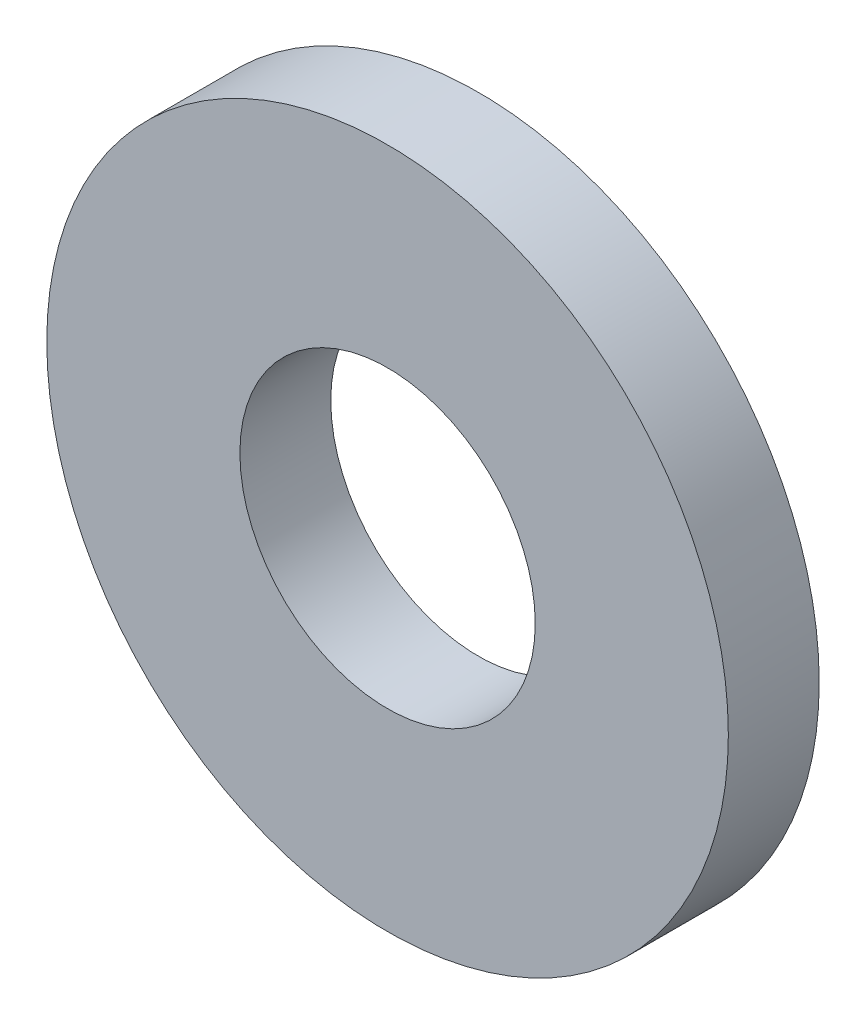
SolidWorks part; units mm, degrees
ref_plane "Alzado" through (0, 0, 0) normal (0, 0, 1) x (1, 0, 0)
ref_plane "Planta" through (0, 0, 0) normal (0, 1, 0) x (1, 0, 0)
ref_plane "Vista lateral" through (0, 0, 0) normal (1, 0, 0) x (0, 0, -1)
sketch "Croquis1" plane through (0, 0, 0) normal (0, 0, 1) x (1, 0, 0)
  circle A0 centre (0, 0) radius 3.25
  circle A1 centre (0, 0) radius 7.5
  dimension "D1" = 6.5
  dimension "D2" = 15
extrude "Saliente-Extruir1" add sketch "Croquis1" along normal blind 2
